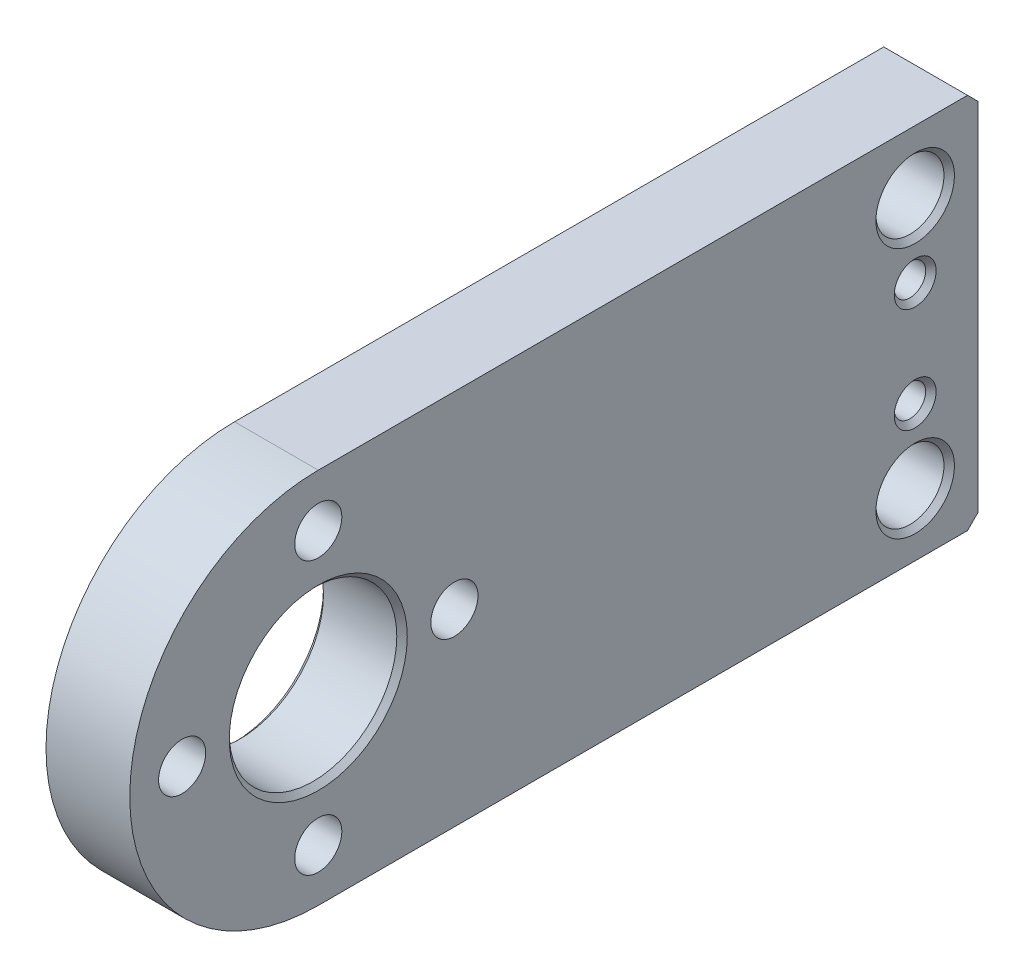
SolidWorks part; units mm, degrees
ref_plane "Front Plane" through (0, 0, 0) normal (0, 0, 1) x (1, 0, 0)
ref_plane "Top Plane" through (0, 0, 0) normal (0, 1, 0) x (1, 0, 0)
ref_plane "Right Plane" through (0, 0, 0) normal (1, 0, 0) x (0, 0, -1)
sketch "Sketch1" plane through (0, 0, 0) normal (1, 0, 0) x (0, 0, -1)
  line L0 (-31.4386, 2.386) -> (31.5614, 2.386) construction
  line L1 (-31.4386, 20.386) -> (31.5614, 20.386)
  line L2 (-31.4386, 20.386) -> (-31.4386, -15.614) construction
  line L3 (-31.4386, -15.614) -> (31.5614, -15.614)
  line L4 (31.5614, 20.386) -> (31.5614, -15.614)
  arc A0 (-31.4386, 20.386) -> (-31.4386, -15.614) centre (-31.4386, 2.386) ccw
  circle A1 centre (-31.4386, 2.386) radius 13 construction
  circle A2 centre (-31.4386, 2.386) radius 8
  circle A3 centre (-31.4386, 15.386) radius 2.25
  circle A4 centre (-18.4386, 2.386) radius 2.25
  circle A5 centre (-31.4386, -10.614) radius 2.25
  circle A6 centre (-44.4386, 2.386) radius 2.25
  circle A7 centre (25.5614, 14.386) radius 3.25
  circle A9 centre (25.5614, 7.386) radius 1.5
  circle A10 centre (25.5614, -2.614) radius 1.5
  circle A11 centre (25.5614, -9.614) radius 3.25
  dimension "D3" = 26
  dimension "D4" = 16
  dimension "D5" = 4.5
  dimension "D10" = 6.5
  dimension "D11" = 3
  dimension "D1" = 63
  dimension "D2" = 36
  dimension "D6" = 6
  dimension "D7" = 6
  dimension "D8" = 12
  dimension "D9" = 5
extrude "Boss-Extrude1" add sketch "Sketch1" along normal blind 8
chamfer "Chamfer1" distance 1 angle 45 2 edges at (4, -15.614, -31.5614) (4, 20.386, -31.5614)
chamfer "Chamfer2" distance 0.5 angle 45 10 edges at (0, -9.614, -22.3114) (8, -9.614, -22.3114) (0, -2.614, -24.0614) (8, -2.614, -24.0614) (0, 7.386, -27.0614) (8, 7.386, -27.0614) (0, 14.386, -28.8114) (8, 14.386, -28.8114) (0, 2.386, 23.4386) (8, 2.386, 23.4386)
